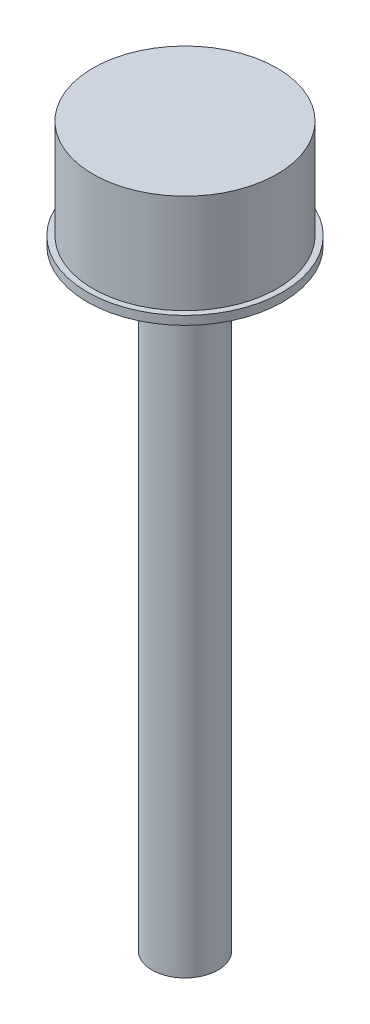
SolidWorks part; units mm, degrees
material "PVC Rigid"
ref_plane "Front" through (0, 0, 0) normal (0, 0, 1) x (1, 0, 0)
ref_plane "Top" through (0, 0, 0) normal (0, 1, 0) x (1, 0, 0)
ref_plane "Right" through (0, 0, 0) normal (1, 0, 0) x (0, 0, -1)
sketch "Sketch1" plane through (0, 0, 0) normal (0, 0, 1) x (1, 0, 0)
  line L0 (0, 0) -> (0, 127)
  line L1 (0, 127) -> (-16.256, 127)
  line L2 (-16.256, 127) -> (-16.256, 109.474)
  line L3 (-16.256, 109.474) -> (-17.272, 109.474)
  line L4 (-17.272, 109.474) -> (-17.272, 107.95)
  line L5 (-17.272, 107.95) -> (-5.842, 107.95)
  line L6 (-5.842, 107.95) -> (-5.842, 0)
  line L7 (-5.842, 0) -> (0, 0)
  dimension "D1" = 127
  dimension "D2" = 19.05
  dimension "D3" = 1.524
  dimension "D4" = 16.256
  dimension "D5" = 17.272
  dimension "D6" = 5.842
revolve "Revolve1" add sketch "Sketch1" angle 360 about L0
